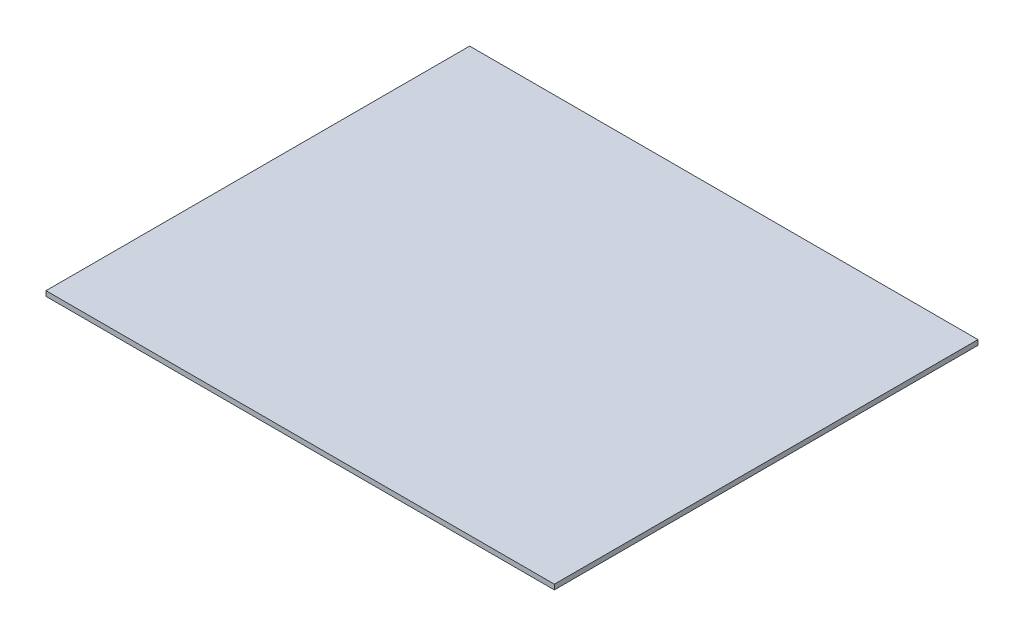
SolidWorks part; units mm, degrees
ref_plane "Front Plane" through (0, 0, 0) normal (0, 0, 1) x (1, 0, 0)
ref_plane "Top Plane" through (0, 0, 0) normal (0, 1, 0) x (1, 0, 0)
ref_plane "Right Plane" through (0, 0, 0) normal (1, 0, 0) x (0, 0, -1)
sketch "Sketch1" plane through (0, 0, 0) normal (0, 1, 0) x (1, 0, 0)
  line L1 (-51, 42.5) -> (51, 42.5)
  line L2 (-51, 42.5) -> (-51, -42.5)
  line L3 (-51, -42.5) -> (51, -42.5)
  line L4 (51, 42.5) -> (51, -42.5)
  line L5 (-51, 42.5) -> (51, -42.5) construction
  line L6 (-51, -42.5) -> (51, 42.5) construction
  point P0 (0, 0)
  dimension "D1" = 85
  dimension "D2" = 102
extrude "Boss-Extrude1" add sketch "Sketch1" along normal mid plane 1
